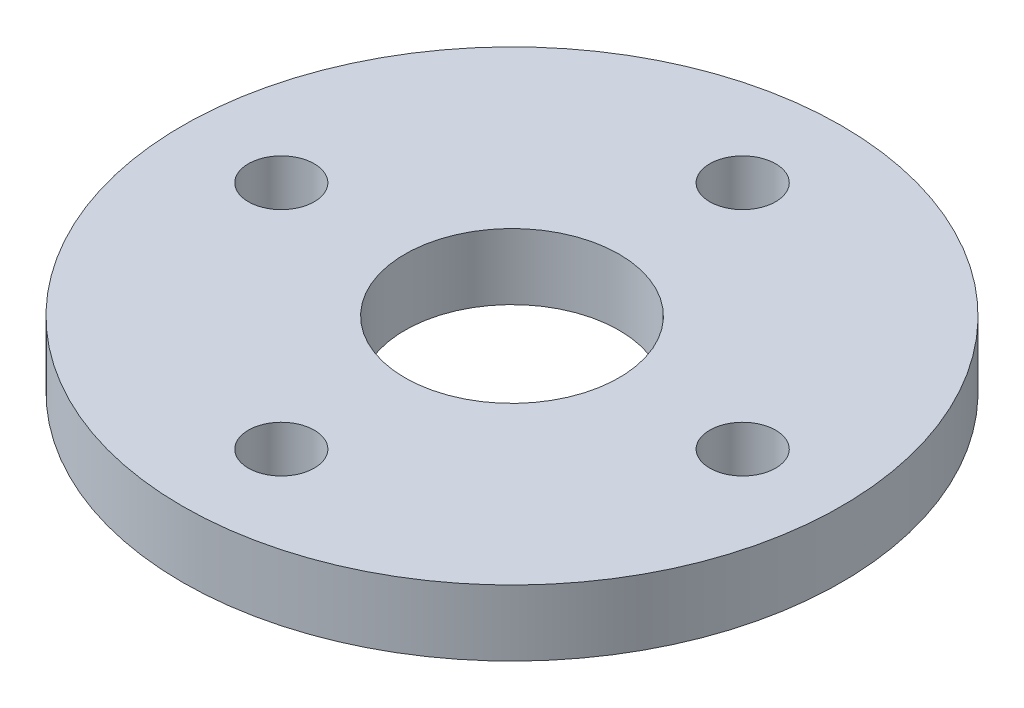
SolidWorks part; units mm, degrees
ref_plane "Front Plane" through (0, 0, 0) normal (0, 0, 1) x (1, 0, 0)
ref_plane "Top Plane" through (0, 0, 0) normal (0, 1, 0) x (1, 0, 0)
ref_plane "Right Plane" through (0, 0, 0) normal (1, 0, 0) x (0, 0, -1)
sketch "Sketch1" plane through (0, 0, 0) normal (0, 1, 0) x (1, 0, 0)
  circle A0 centre (0, 0) radius 3.25
  circle A1 centre (0, 0) radius 10
  circle A2 centre (0, 0) radius 7 construction
  circle A3 centre (0, 7) radius 1
  circle A4 centre (7, 0) radius 1
  circle A5 centre (0, -7) radius 1
  circle A6 centre (-7, 0) radius 1
  dimension "D1" = 20
  dimension "D2" = 6.5
  dimension "D3" = 2
  dimension "D4" = 14
  dimension "D5" = 4
extrude "Boss-Extrude1" add sketch "Sketch1" along normal blind 2
